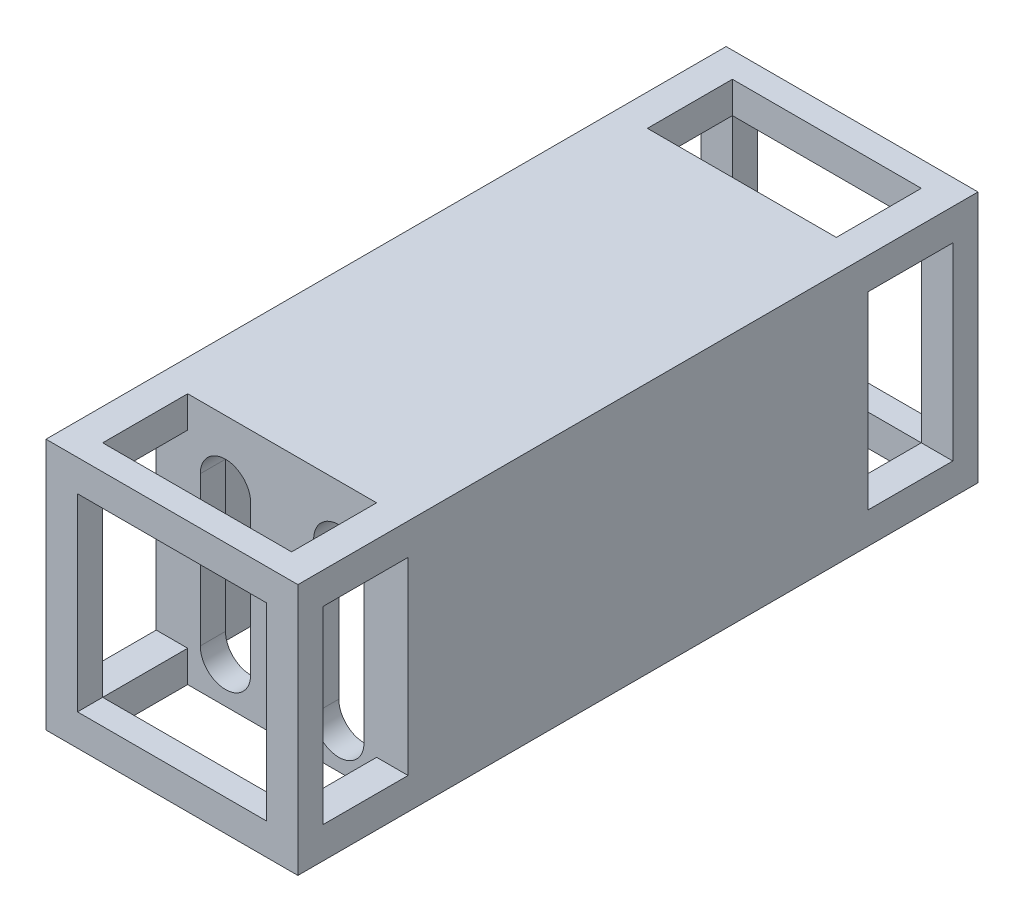
SolidWorks part; units mm, degrees
ref_plane "Plano frontal" through (0, 0, 0) normal (0, 0, 1) x (1, 0, 0)
ref_plane "Plano superior" through (0, 0, 0) normal (0, 1, 0) x (1, 0, 0)
ref_plane "Plano direito" through (0, 0, 0) normal (1, 0, 0) x (0, 0, -1)
sketch "Esboço1" plane through (0, 0, 0) normal (0, 0, 1) x (1, 0, 0)
  line L0 (-9, 9) -> (-9, 27) construction
  line L1 (20, 0) -> (-20, 0)
  line L2 (20, 0) -> (20, 40)
  line L3 (20, 40) -> (-20, 40)
  line L4 (-20, 0) -> (-20, 40)
  line L5 (0, 9) -> (0, 27) construction
  line L6 (0, 40) -> (0, 0) construction
  line L7 (-9, 27) -> (9, 27) construction
  line L8 (9, 27) -> (9, 9) construction
  line L9 (9, 9) -> (0, 9) construction
  line L10 (-9, 36) -> (9, 36)
  line L11 (18, 27) -> (18, 0)
  line L12 (-18, 9) -> (-18, 27)
  line L13 (-18, 9) -> (-18, 0)
  arc A0 (-9, 36) -> (-18, 27) centre (-9, 27) ccw
  arc A1 (18, 27) -> (9, 36) centre (9, 27) ccw
  point P0 (0, 0)
  dimension "D3" = 18
  dimension "D4" = 18
  dimension "D1" = 40
extrude "Ressalto-extrusão1" add sketch "Esboço1" along normal blind 65 contours A1 L11 L1 L2 L3 L4 L13 L12 A0 L10
sketch "Esboço2" plane through (0, 0, 0) normal (0, 0, -1) x (-1, 0, 0)
  line L0 (-9, 30) -> (-9, 6) construction
  line L1 (-20, 40) -> (20, 40)
  line L2 (-20, 40) -> (-20, 0)
  line L3 (-20, 0) -> (20, 0)
  line L4 (20, 40) -> (20, 0)
  line L5 (-5, 30) -> (-5, 6)
  line L6 (-13, 30) -> (-13, 6)
  line L7 (9, 30) -> (9, 6.321) construction
  line L8 (13, 30) -> (13, 6.321)
  line L9 (5, 30) -> (5, 6.321)
  line L10 (-18, 27) -> (-18, 0) construction
  line L11 (9, 36) -> (-9, 36) construction
  arc A0 (-5, 30) -> (-13, 30) centre (-9, 30) ccw
  arc A1 (-13, 6) -> (-5, 6) centre (-9, 6) ccw
  arc A2 (13, 30) -> (5, 30) centre (9, 30) ccw
  arc A3 (5, 6.321) -> (13, 6.321) centre (9, 6.321) ccw
  point P8 (-9, 18)
  point P13 (9, 18.1605)
  dimension "D1" = 18
  dimension "D2" = 9
  dimension "D3" = 6
  dimension "D4" = 6.321
  dimension "D5" = 6
  dimension "D6" = 6
  dimension "D7" = 8
  dimension "D8" = 8
extrude "Ressalto-extrusão2" add sketch "Esboço2" along normal blind 4
ref_plane "Plano1" through (0, 0, 32.5) normal (0, 0, 1) x (1, 0, 0)
sketch "Esboço4" plane through (0, 0, -4) normal (0, 0, -1) x (-1, 0, 0)
  line L0 (-20, 40) -> (-20, 0) construction
  line L1 (20, 40) -> (15, 40)
  line L2 (20, 40) -> (20, 35)
  line L3 (20, 35) -> (15, 35)
  line L4 (15, 40) -> (15, 35)
  line L5 (20, 0) -> (15, 0)
  line L6 (20, 0) -> (20, 5)
  line L7 (20, 5) -> (15, 5)
  line L8 (15, 0) -> (15, 5)
  line L9 (-20, 40) -> (-15, 40)
  line L10 (-20, 40) -> (-20, 35)
  line L11 (-20, 35) -> (-15, 35)
  line L12 (-15, 40) -> (-15, 35)
  line L14 (-20, 0) -> (-15, 0)
  line L15 (-20, 0) -> (-20, 5)
  line L16 (-20, 5) -> (-15, 5)
  line L17 (-15, 0) -> (-15, 5)
  dimension "D1" = 5
extrude "Ressalto-extrusão3" add sketch "Esboço4" along normal blind 13.5
sketch "Esboço5" plane through (0, 0, -17.5) normal (0, 0, -1) x (-1, 0, 0)
  line L1 (20, 40) -> (-20, 40)
  line L2 (20, 40) -> (20, 0)
  line L3 (20, 0) -> (-20, 0)
  line L4 (-20, 40) -> (-20, 0)
  line L5 (-15, 35) -> (15, 35)
  line L6 (-15, 35) -> (-15, 5)
  line L7 (-15, 5) -> (15, 5)
  line L8 (15, 35) -> (15, 5)
extrude "Ressalto-extrusão4" add sketch "Esboço5" along normal blind 4
mirror "Espelhar1" about plane through (0, 0, 32.5) normal (0, 0, 1) of "Ressalto-extrusão4", "Ressalto-extrusão3", "Ressalto-extrusão2"
